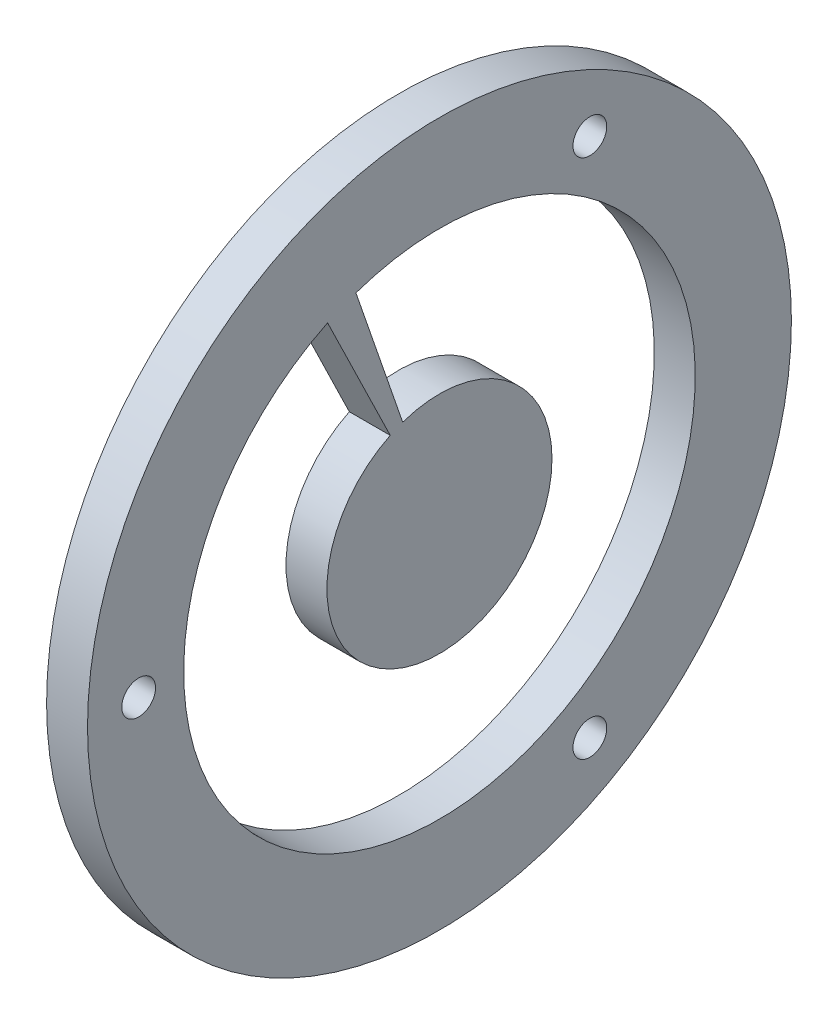
SolidWorks part; units mm, degrees
ref_plane "Front Plane" through (0, 0, 0) normal (0, 0, 1) x (1, 0, 0)
ref_plane "Top Plane" through (0, 0, 0) normal (0, 1, 0) x (1, 0, 0)
ref_plane "Right Plane" through (0, 0, 0) normal (1, 0, 0) x (0, 0, -1)
sketch "Axial profile (mm)" plane through (0, 0, 0) normal (0, 0, 1) x (1, 0, 0)
  line L0 (-110, 0) -> (75, 0) construction
  line L1 (159.7, 0) -> (163.7, 0)
  line L2 (163.7, 0) -> (163.7, 34.4)
  line L3 (163.7, 34.4) -> (159.7, 34.4)
  line L4 (159.7, 34.4) -> (159.7, 0)
revolve "Full revolution" add sketch "Axial profile (mm)" angle 360 about L0
sketch "Sketch2" plane through (0, 0, 0) normal (1, 0, 0) x (0, 0, -1)
  circle A0 centre (-29.4, 0) radius 1.65
  circle A1 centre (14.7, -25.4611) radius 1.65
  circle A2 centre (14.7, 25.4611) radius 1.65
extrude "Axial holes" cut sketch "Sketch2" against normal through all and the other way through all
sketch "Sketch3" plane through (0, 0, 0) normal (1, 0, 0) x (0, 0, -1)
  line L0 (-10.9349, 22.4817) -> (-4.8113, 9.892)
  line L1 (-8.1649, 23.6291) -> (-3.5925, 10.3968)
  arc A0 (-10.9349, 22.4817) -> (-8.1649, 23.6291) centre (0, 0) ccw
  arc A1 (-4.8113, 9.892) -> (-3.5925, 10.3968) centre (0, 0) ccw
extrude "C-shaped coolant passage and integral divider" cut sketch "Sketch3" against normal through all and the other way through all
